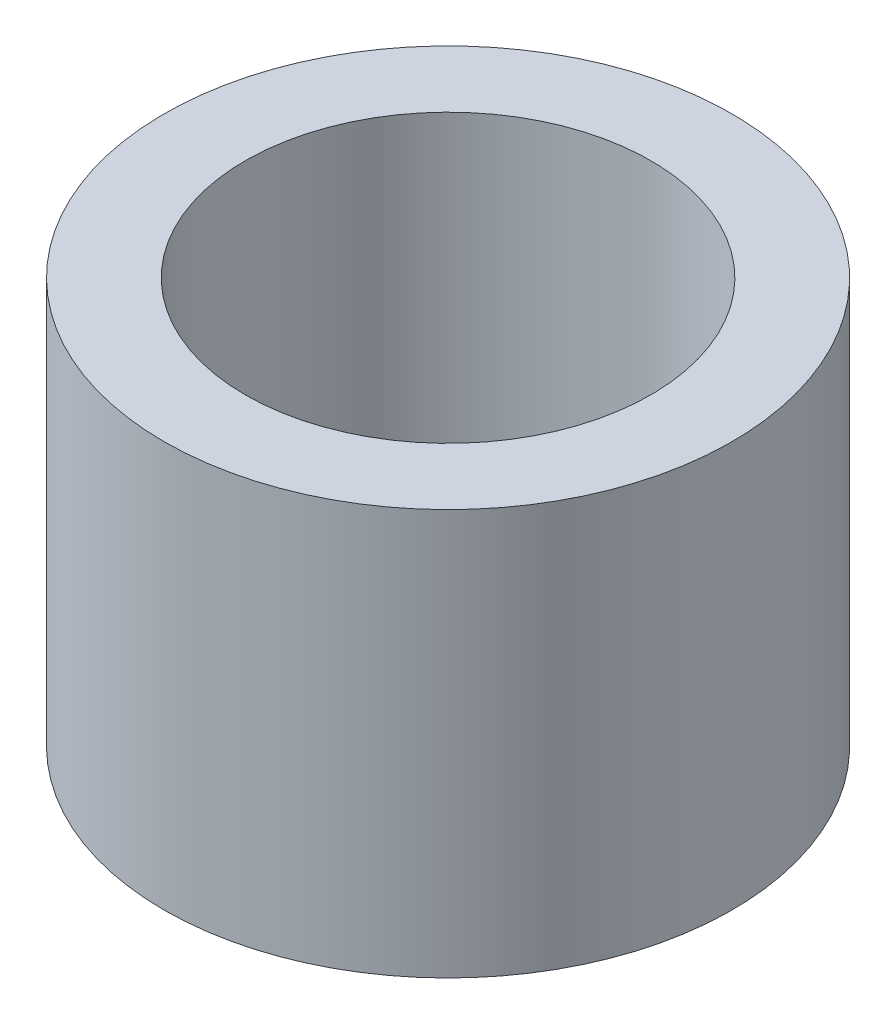
SolidWorks part; units mm, degrees
ref_plane "Alzado" through (0, 0, 0) normal (0, 0, 1) x (1, 0, 0)
ref_plane "Planta" through (0, 0, 0) normal (0, 1, 0) x (1, 0, 0)
ref_plane "Vista lateral" through (0, 0, 0) normal (1, 0, 0) x (0, 0, -1)
sketch "Croquis1" plane through (0, 0, 0) normal (0, 1, 0) x (1, 0, 0)
  circle A0 centre (0, 0) radius 3.5
  circle A1 centre (0, 0) radius 2.5
  dimension "D1" = 7
  dimension "D2" = 5
extrude "Saliente-Extruir1" add sketch "Croquis1" along normal blind 5
